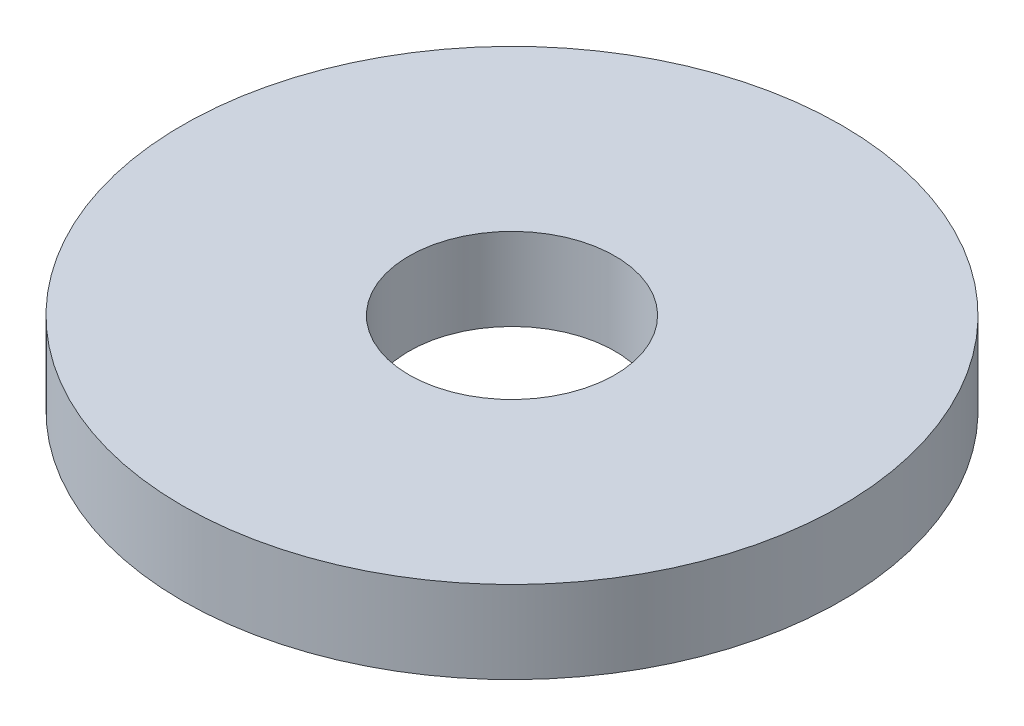
SolidWorks part; units mm, degrees
ref_plane "Front Plane" through (0, 0, 0) normal (0, 0, 1) x (1, 0, 0)
ref_plane "Top Plane" through (0, 0, 0) normal (0, 1, 0) x (1, 0, 0)
ref_plane "Right Plane" through (0, 0, 0) normal (1, 0, 0) x (0, 0, -1)
sketch "Sketch1" plane through (0, 0, 0) normal (0, 1, 0) x (1, 0, 0)
  circle A0 centre (0, 0) radius 40
  circle A1 centre (0, 0) radius 12.5
  dimension "D1" = 80
  dimension "D2" = 25
extrude "Boss-Extrude1" add sketch "Sketch1" along normal blind 10
equation "\"Diámetro exterior\"= 80"
equation "\"D1@Sketch1\"=\"Diámetro exterior\""
equation "\"Diámetro interior\"= 25"
equation "\"D2@Sketch1\"=\"Diámetro interior\""
equation "\"Grosor de Tapa\"= 10"
equation "\"D1@Boss-Extrude1\"=\"Grosor de Tapa\""
